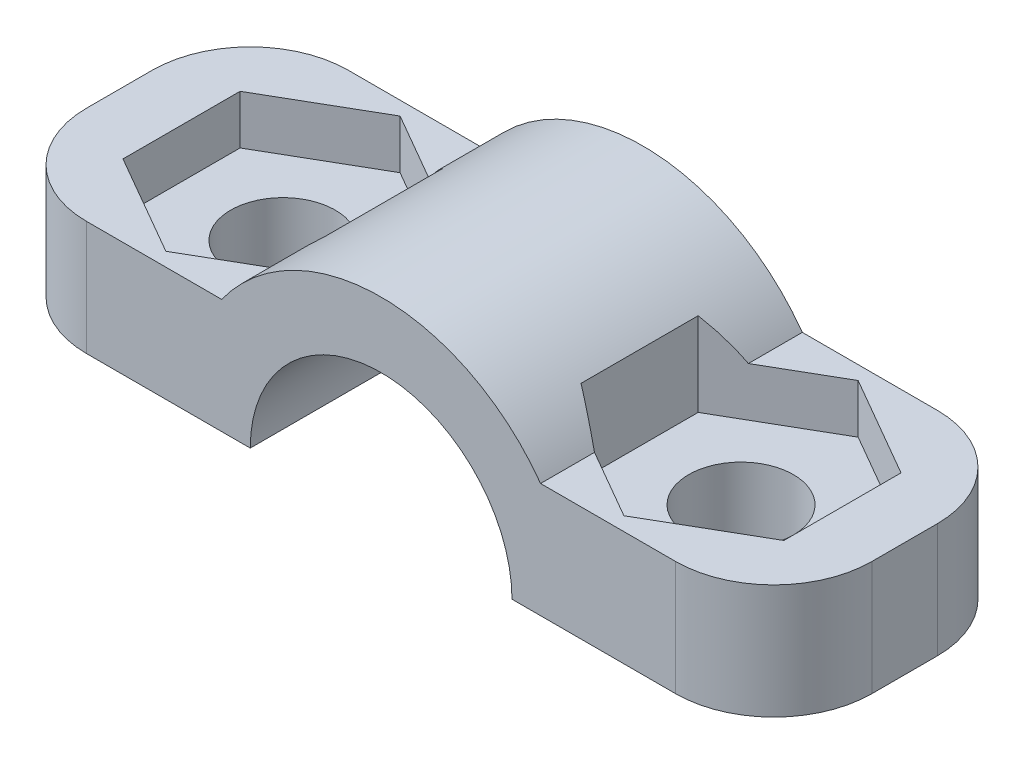
SolidWorks part; units mm, degrees
material "ABS"
ref_plane "Front Plane" through (0, 0, 0) normal (0, 0, 1) x (1, 0, 0)
ref_plane "Top Plane" through (0, 0, 0) normal (0, 1, 0) x (1, 0, 0)
ref_plane "Right Plane" through (0, 0, 0) normal (1, 0, 0) x (0, 0, -1)
sketch "Sketch1" plane through (0, 0, 0) normal (0, 0, 1) x (1, 0, 0)
  line L0 (-4, 0) -> (-12, 0)
  line L1 (-12, 0) -> (-12, 6)
  line L2 (-12, 6) -> (12, 6)
  line L3 (12, 6) -> (12, 0)
  line L4 (12, 0) -> (4, 0)
  arc A0 (4, 0) -> (-4, 0) centre (0, 0) ccw
  point P6 (11.0432, -1.6541)
  point P9 (0, 0)
  point P10 (0, 6)
  dimension "D2" = 4
  dimension "D1" = 24
  dimension "D3" = 6
extrude "Boss-Extrude1" add sketch "Sketch1" along normal blind 8
sketch "Sketch3" plane through (0, 0, 0) normal (0, -1, 0) x (1, 0, 0)
  line L0 (4, 8) -> (4, 0) construction
  line L3 (-4, 8) -> (-4, 0) construction
  circle A0 centre (7, 4) radius 1.6
  circle A1 centre (-7, 4) radius 1.6
  point P4 (0, 0)
  point P7 (4, 4)
  point P8 (0, 0)
  point P12 (0, 0)
  point P16 (0, 0)
  dimension "D1" = 3.2
  dimension "D2" = 3
  dimension "D3" = 3
extrude "Cut-Extrude1" cut sketch "Sketch3" against normal up to next
sketch "Sketch4" plane through (0, 6, 0) normal (0, 1, 0) x (1, 0, 0)
  line L14 (7, -0.4204) -> (3.9, -2.2102)
  line L15 (3.9, -2.2102) -> (3.9, -5.7898)
  line L16 (3.9, -5.7898) -> (7, -7.5796)
  line L17 (7, -7.5796) -> (10.1, -5.7898)
  line L18 (10.1, -5.7898) -> (10.1, -2.2102)
  line L19 (10.1, -2.2102) -> (7, -0.4204)
  line L20 (-7, -0.4204) -> (-10.1, -2.2102)
  line L21 (-10.1, -2.2102) -> (-10.1, -5.7898)
  line L22 (-10.1, -5.7898) -> (-7, -7.5796)
  line L23 (-7, -7.5796) -> (-3.9, -5.7898)
  line L24 (-3.9, -5.7898) -> (-3.9, -2.2102)
  line L25 (-3.9, -2.2102) -> (-7, -0.4204)
  circle A0 centre (7, -4) radius 3.1 construction
  circle A1 centre (-7, -4) radius 3.1 construction
  dimension "D1" = 6.2
extrude "Cut-Extrude2" cut sketch "Sketch4" against normal offset from surface (4 mm away) 2 up to face at (8.6, 0, 4)
fillet "Fillet1" radius 3 4 edges at (-12, 3, 8) (-12, 3, 0) (12, 3, 8) (12, 3, 0)
sketch "Sketch5" plane through (0, 0, 0) normal (0, 0, -1) x (-1, 0, 0)
  line L2 (-12, 3.5) -> (-4.8734, 3.5)
  line L3 (-12, 0) -> (-12, 6) construction
  line L4 (12, 6) -> (12, 0) construction
  line L5 (4.8734, 3.5) -> (12, 3.5)
  line L6 (-4, 0) -> (-9, 0) construction
  line L7 (-12, 3.5) -> (-12, 6)
  line L8 (-12, 6) -> (12, 6)
  line L9 (12, 6) -> (12, 3.5)
  arc A0 (-4.8734, 3.5) -> (4.8734, 3.5) centre (0, 0) cw
  line M3 (9, 0) -> (9, 6)
  line M4 (9, 6) -> (-9, 6)
  line M5 (-9, 6) -> (-9, 0)
  dimension "D1" = 6
  dimension "D2" = 3.5
extrude "Cut-Extrude3" cut sketch "Sketch5" against normal through all contours L2 A0 L8 M5 | L8 L7 L2 M5 | A0 L5 M4 M3 | L9 L8 L5 M3
